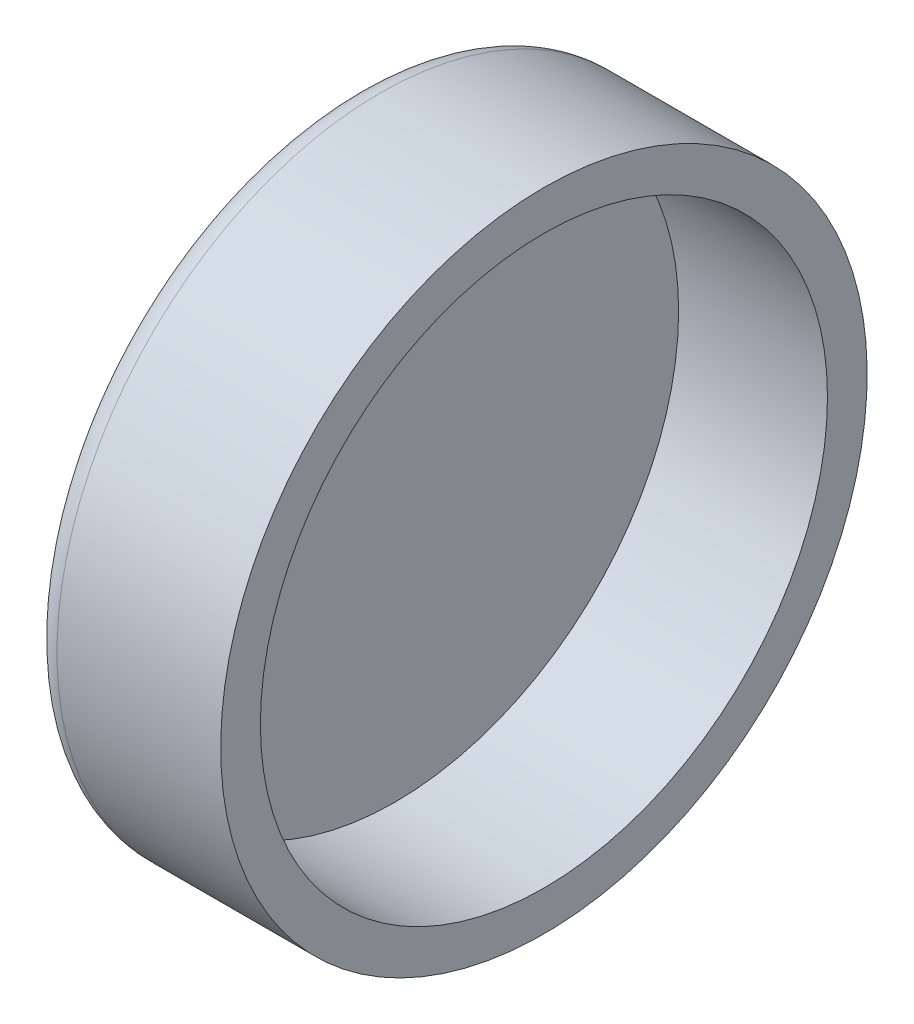
SolidWorks part; units mm, degrees
ref_plane "Front" through (0, 0, 0) normal (0, 0, 1) x (1, 0, 0)
ref_plane "Top" through (0, 0, 0) normal (0, 1, 0) x (1, 0, 0)
ref_plane "Right" through (0, 0, 0) normal (1, 0, 0) x (0, 0, -1)
sketch "Croquis2" plane through (0, 0, 0) normal (0, 0, 1) x (1, 0, 0)
  line L0 (0, 57.15) -> (-30, 57.15)
  line L1 (-30, 57.15) -> (-30, 0)
  line L2 (-30, 0) -> (-38, 0)
  line L3 (0, 57.15) -> (0, 65.15)
  line L5 (0, 65.15) -> (-38, 65.15)
  line L6 (-38, 65.15) -> (-38, 0)
  dimension "D1" = 57.15
  dimension "D2" = 30
  dimension "D3" = 8
  dimension "D4" = 8
revolve "Revolución1" add sketch "Croquis2" angle 360 about L2
fillet "Redondeo1" radius 5 1 edges at (-38, 65.15, 0)
